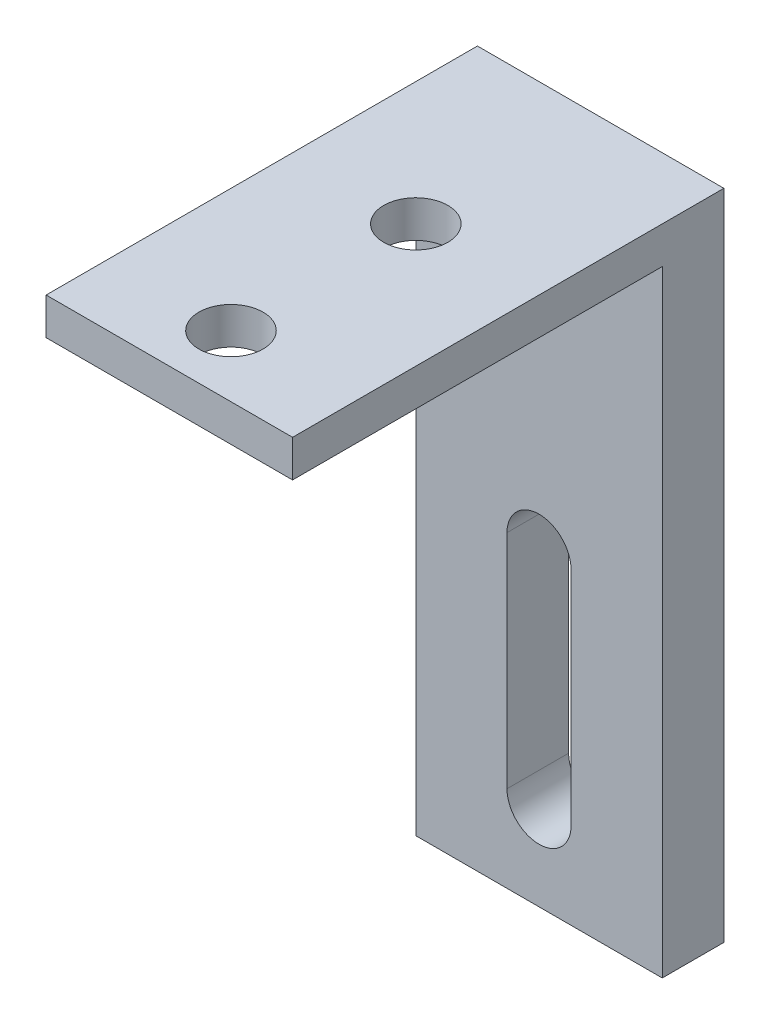
SolidWorks part; units mm, degrees
ref_plane "Front Plane" through (0, 0, 0) normal (0, 0, 1) x (1, 0, 0)
ref_plane "Top Plane" through (0, 0, 0) normal (0, 1, 0) x (1, 0, 0)
ref_plane "Right Plane" through (0, 0, 0) normal (1, 0, 0) x (0, 0, -1)
sketch "Sketch1" plane through (0, 0, 0) normal (0, 1, 0) x (1, 0, 0)
  line L1 (-10, 10) -> (10, 10)
  line L2 (-10, 10) -> (-10, -10)
  line L3 (-10, -10) -> (10, -10)
  line L4 (10, 10) -> (10, -10)
  line L5 (-10, 10) -> (10, -10) construction
  line L6 (-10, -10) -> (10, 10) construction
  circle A0 centre (0, 0) radius 2.6
  point P0 (0, 0)
  dimension "D2" = 5.2
  dimension "D1" = 20
extrude "Boss-Extrude2" add sketch "Sketch1" along normal blind 3
sketch "Sketch2" plane through (0, 0, 10) normal (0, 0, 1) x (1, 0, 0)
  line L4 (-10, 0) -> (10, 0)
  line L5 (10, 0) -> (10, 3)
  line L6 (10, 3) -> (-10, 3)
  line L7 (-10, 3) -> (-10, 0)
  line L8 (-10, 0) -> (10, 0)
  line L9 (10, 0) -> (10, 3)
  line L10 (10, 3) -> (-10, 3)
  line L11 (-10, 3) -> (-10, 0)
  dimension "D1" = 0
extrude "Boss-Extrude3" add sketch "Sketch2" along normal blind 10
sketch "Sketch4" plane through (0, 3, 0) normal (0, 1, 0) x (1, 0, 0)
  line L0 (0, 0) -> (0, -15)
  circle A0 centre (0, -15) radius 2.6
  dimension "D2" = 5.2
  dimension "D1" = 15
extrude "Cut-Extrude1" cut sketch "Sketch4" against normal blind 10
sketch "Sketch6" plane through (0, 0, -10) normal (0, 0, -1) x (-1, 0, 0)
  line L4 (-10, 0) -> (10, 0)
  line L5 (10, 0) -> (10, 3)
  line L6 (10, 3) -> (-10, 3)
  line L7 (-10, 3) -> (-10, 0)
  line L8 (-10, 0) -> (10, 0)
  line L9 (10, 0) -> (10, 3)
  line L10 (10, 3) -> (-10, 3)
  line L11 (-10, 3) -> (-10, 0)
  dimension "D1" = 0
extrude "Boss-Extrude5" add sketch "Sketch6" along normal blind 5
sketch "Sketch7" plane through (0, 0, 0) normal (0, -1, 0) x (1, 0, 0)
  line L1 (10, -15) -> (-10, -15)
  line L2 (10, -15) -> (10, -10)
  line L3 (10, -10) -> (-10, -10)
  line L4 (-10, -15) -> (-10, -10)
  line L5 (-10, -15) -> (-10, 20) construction
  dimension "D1" = 5
  dimension "D2" = 20
extrude "Boss-Extrude6" add sketch "Sketch7" along normal blind 50
sketch "Sketch8" plane through (0, 0, -15) normal (0, 0, -1) x (-1, 0, 0)
  line L0 (0, 0) -> (0, -50) construction
  line L1 (10, -50) -> (-10, -50) construction
  line L2 (-2.6, -25) -> (-2.6, -43)
  line L3 (2.6, -25) -> (2.6, -43)
  arc A0 (2.6, -25) -> (-2.6, -25) centre (0, -25) ccw
  arc A1 (-2.6, -43) -> (2.6, -43) centre (0, -43) ccw
  point P6 (-16.714, -40.4417)
  point P13 (3.99, -43)
  dimension "D1" = 5.2
  dimension "D2" = 5.2
  dimension "D3" = 18
  dimension "D4" = 18
  dimension "D5" = 18
extrude "Cut-Extrude2" cut sketch "Sketch8" against normal blind 5 contours L2 A1 L3 A0
